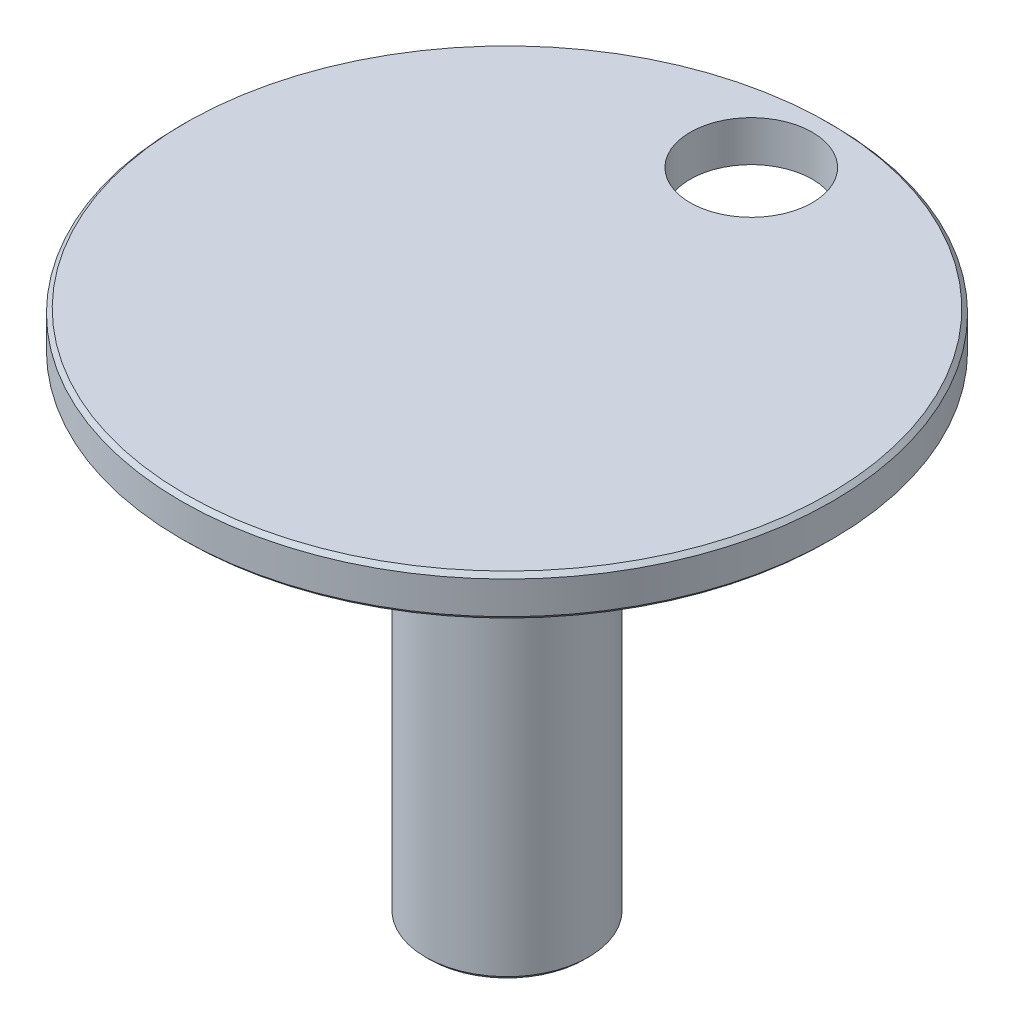
SolidWorks part; units mm, degrees
ref_plane "Front Plane" through (0, 0, 0) normal (0, 0, 1) x (1, 0, 0)
ref_plane "Top Plane" through (0, 0, 0) normal (0, 1, 0) x (1, 0, 0)
ref_plane "Right Plane" through (0, 0, 0) normal (1, 0, 0) x (0, 0, -1)
sketch "Sketch1" plane through (0, 0, 0) normal (0, 1, 0) x (1, 0, 0)
  circle A0 centre (0, 0) radius 2
  dimension "D1" = 4
extrude "Boss-Extrude1" add sketch "Sketch1" along normal blind 11.6
sketch "Sketch2" plane through (0, 11.6, 0) normal (0, 1, 0) x (1, 0, 0)
  circle A0 centre (0, 0) radius 4
  dimension "D1" = 8
extrude "Boss-Extrude2" add sketch "Sketch2" along normal blind 0.3
sketch "Sketch3" plane through (0, 11.9, 0) normal (0, 1, 0) x (1, 0, 0)
  circle A0 centre (0, 0) radius 8
  dimension "D1" = 16
extrude "Boss-Extrude3" add sketch "Sketch3" along normal blind 1
sketch "Sketch4" plane through (0, 0, 0) normal (0, -1, 0) x (1, 0, 0)
  circle A0 centre (0, 0) radius 1.5
  dimension "D1" = 3
extrude "Cut-Extrude1" cut sketch "Sketch4" against normal blind 8.5 contours A0
sketch "Sketch5" plane through (0, 11.9, 0) normal (0, -1, 0) x (1, 0, 0)
  line L0 (0, 0) -> (0, -8)
  circle A0 centre (0, -6) radius 1.5
  circle A1 centre (0, 0) radius 8 construction
  circle A2 centre (0, 0) radius 4 construction
  circle A3 centre (0, 0) radius 4
  circle A4 centre (0, 0) radius 8
  point P12 (0, -4.5)
  point P13 (0, -4)
  point P14 (0, -7.5)
  dimension "D1" = 3
  dimension "D2" = 0.5
extrude "Cut-Extrude2" cut sketch "Sketch5" against normal through all contours L0 A0 | L0 A0
chamfer "Chamfer1" distance 0.1 angle 45 4 edges at (0, 0, 2) (0, 11.6, 2) (0, 11.9, 8) (0, 12.9, 8)
